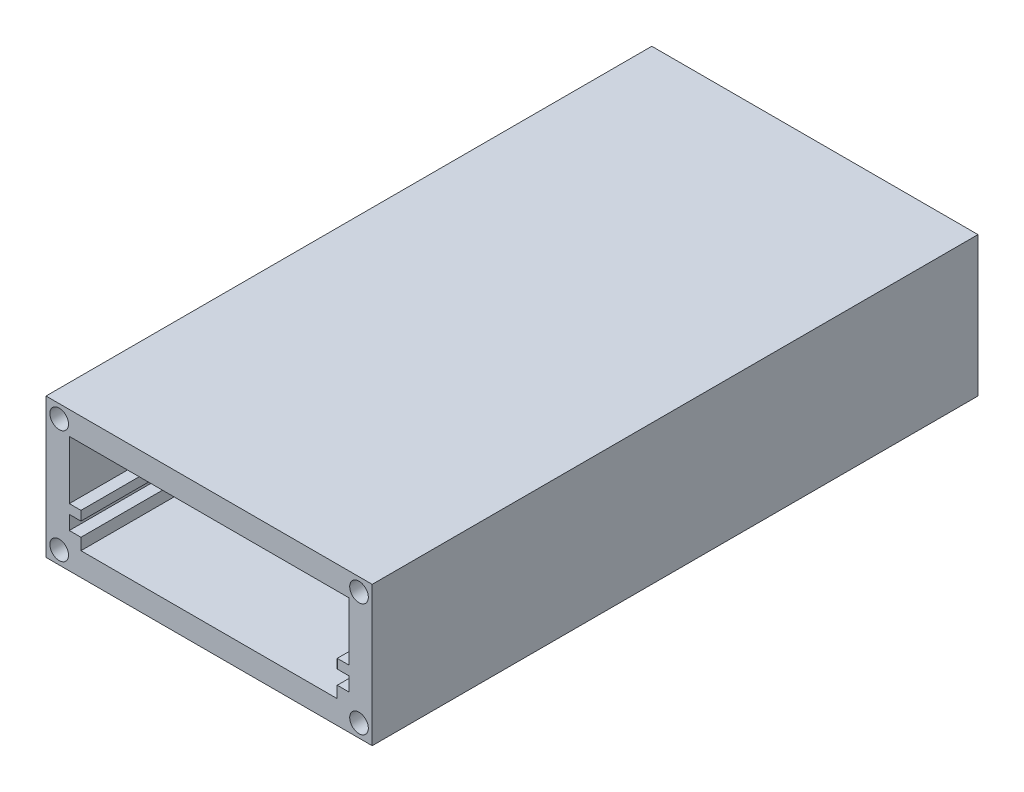
SolidWorks part; units mm, degrees
ref_plane "Front Plane" through (0, 0, 0) normal (0, 0, 1) x (1, 0, 0)
ref_plane "Top Plane" through (0, 0, 0) normal (0, 1, 0) x (1, 0, 0)
ref_plane "Right Plane" through (0, 0, 0) normal (1, 0, 0) x (0, 0, -1)
sketch "Sketch1" plane through (0, 0, 0) normal (0, 1, 0) x (1, 0, 0)
  line L5 (-5, 130) -> (-5, 0)
  line L6 (-5, 0) -> (0, 0)
  line L7 (0, 0) -> (65, 0)
  line L8 (65, 130) -> (65, 0)
  line L11 (-5, 130) -> (65, 130)
extrude "Boss-Extrude2" add sketch "Sketch1" along normal blind 30
sketch "Sketch3" plane through (0, 0, 0) normal (0, 0, 1) x (1, 0, 0)
  line L8 (24.7381, 25) -> (0, 25)
  line L9 (0, 25) -> (0, 5)
  line L10 (0, 5) -> (60, 5)
  line L11 (60, 5) -> (60, 25)
  line L12 (60, 25) -> (24.7381, 25)
extrude "Cut-Extrude1" cut sketch "Sketch3" against normal blind 125 contours L8 L9 L10 L11 L12
sketch "Sketch4" plane through (0, 0, 0) normal (1, 0, 0) x (0, 0, -1)
  line L3 (125, 25) -> (125, 5) construction
  line L7 (0, 10.5) -> (125, 10.5)
  line L8 (0, 25) -> (0, 5) construction
  line L9 (125, 10.5) -> (125, 12.5)
  line L10 (125, 12.5) -> (0, 12.5)
  line L11 (0, 12.5) -> (0, 10.5)
  line L13 (125, 7.5) -> (0, 7.5)
  line L14 (0, 7.5) -> (0, 5)
  line L15 (0, 5) -> (125, 5)
  line L17 (125, 5) -> (125, 7.5)
extrude "Boss-Extrude4" add sketch "Sketch4" along normal blind 2.5
sketch "Sketch5" plane through (60, 0, 0) normal (-1, 0, 0) x (0, 0, 1)
  line L0 (-125, 5) -> (-125, 7.5)
  line L1 (-125, 5) -> (-125, 25) construction
  line L2 (-125, 7.5) -> (0, 7.5)
  line L3 (0, 5) -> (0, 25) construction
  line L4 (0, 7.5) -> (0, 5)
  line L5 (0, 5) -> (-125, 5)
  line L7 (-125, 10.5) -> (0, 10.5)
  line L8 (0, 10.5) -> (0, 12.5)
  line L9 (0, 12.5) -> (-125, 12.5)
  line L10 (-125, 12.5) -> (-125, 10.5)
extrude "Boss-Extrude5" add sketch "Sketch5" along normal blind 2.5
sketch "Sketch6" plane through (0, 0, 0) normal (0, 0, 1) x (1, 0, 0)
  circle A0 centre (-2.1716, 27.1716) radius 2
  circle A1 centre (62.1716, 27.1716) radius 2
  circle A2 centre (62.1716, 2.8284) radius 2
  circle A3 centre (-2.1716, 2.8284) radius 2
extrude "Cut-Extrude2" cut sketch "Sketch6" against normal blind 20 contours A0 | A3 | A2 | A1
